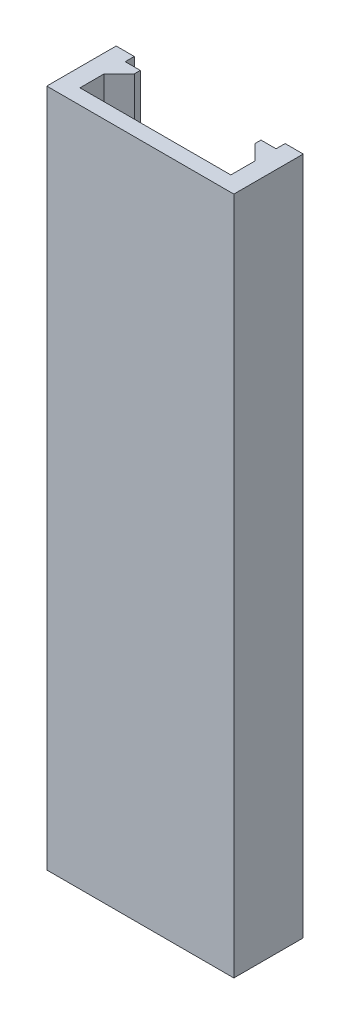
SolidWorks part; units mm, degrees
ref_plane "Přední rovina" through (0, 0, 0) normal (0, 0, 1) x (1, 0, 0)
ref_plane "Horní rovina" through (0, 0, 0) normal (0, 1, 0) x (1, 0, 0)
ref_plane "Pravá rovina" through (0, 0, 0) normal (1, 0, 0) x (0, 0, -1)
sketch "Skica1" plane through (0, 0, 0) normal (0, 1, 0) x (1, 0, 0)
  line L0 (-5, 0) -> (5, 0)
  line L1 (0, -1000) -> (0, 49000) construction
  line L2 (-5, 0) -> (-5, 1.6)
  line L3 (-5, 1.6) -> (-4, 2.6)
  line L4 (-4, 2.6) -> (-4, 3)
  line L6 (-6.2, 3.6) -> (-6.2, -1)
  line L7 (-6.2, -1) -> (6.2, -1)
  line L8 (0, -1) -> (0, 0) construction
  line L9 (-4, 3) -> (-5, 3)
  line L10 (-5, 3) -> (-5, 3.6)
  line L11 (-5, 3.6) -> (-6.2, 3.6)
  line L12 (5, 0) -> (5, 1.6)
  line L13 (5, 1.6) -> (4, 2.6)
  line L14 (4, 2.6) -> (4, 3)
  line L15 (4, 3) -> (5, 3)
  line L16 (5, 3) -> (5, 3.6)
  line L17 (6.2, 3.6) -> (6.2, -1)
  line L18 (5, 3.6) -> (6.2, 3.6)
  dimension "D2" = 0.4
  dimension "D1" = 5
  dimension "D3" = 1
  dimension "D4" = 1.2
  dimension "D5" = 1
  dimension "D6" = 1.6
  dimension "D7" = 1
  dimension "D8" = 0.6
extrude "Přidat vysunutím1" add sketch "Skica1" along normal blind 45
